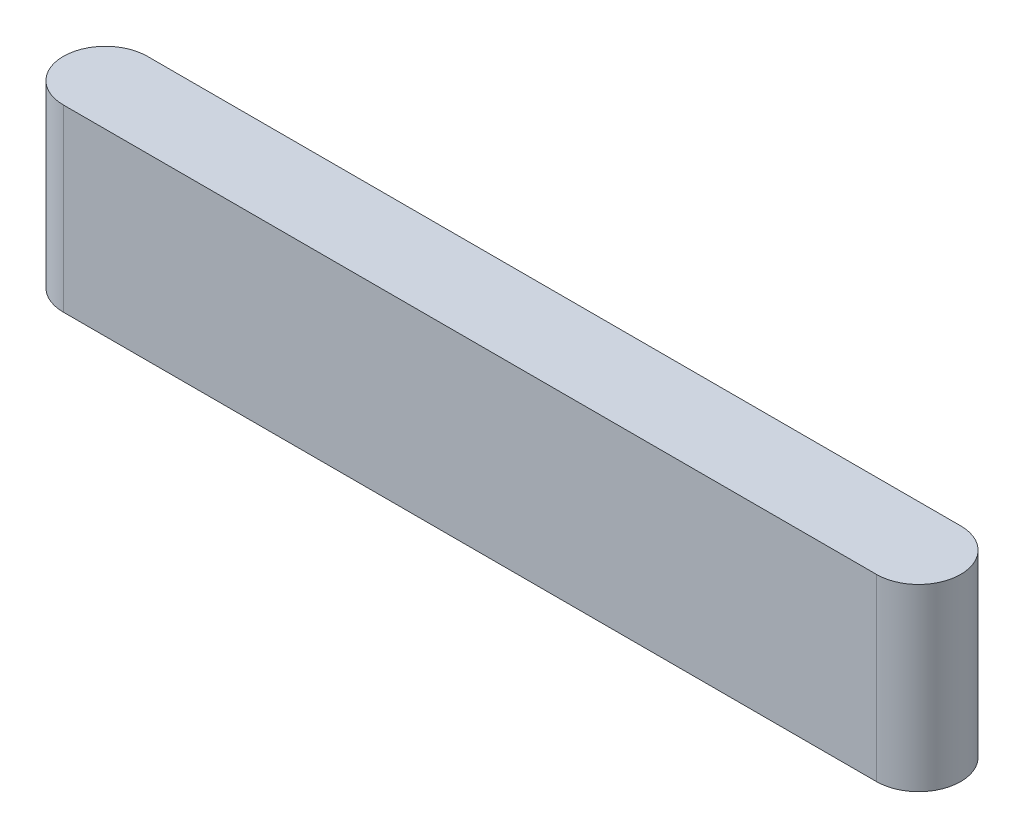
SolidWorks part; units mm, degrees
ref_plane "Front Plane" through (0, 0, 0) normal (0, 0, 1) x (1, 0, 0)
ref_plane "Top Plane" through (0, 0, 0) normal (0, 1, 0) x (1, 0, 0)
ref_plane "Right Plane" through (0, 0, 0) normal (1, 0, 0) x (0, 0, -1)
sketch "Sketch1" plane through (0, 0, 0) normal (0, 1, 0) x (1, 0, 0)
  line L0 (0, 0) -> (14.5, 0) construction
  line L1 (0, 0.75) -> (14.5, 0.75)
  line L2 (0, -0.75) -> (14.5, -0.75)
  arc A0 (0, 0.75) -> (0, -0.75) centre (0, 0) ccw
  arc A1 (14.5, -0.75) -> (14.5, 0.75) centre (14.5, 0) ccw
  point P3 (7.25, 0)
  dimension "D2" = 14.5
  dimension "D3" = 0.75
  dimension "D1" = 1.5
extrude "Boss-Extrude1" add sketch "Sketch1" along normal blind 3.2
